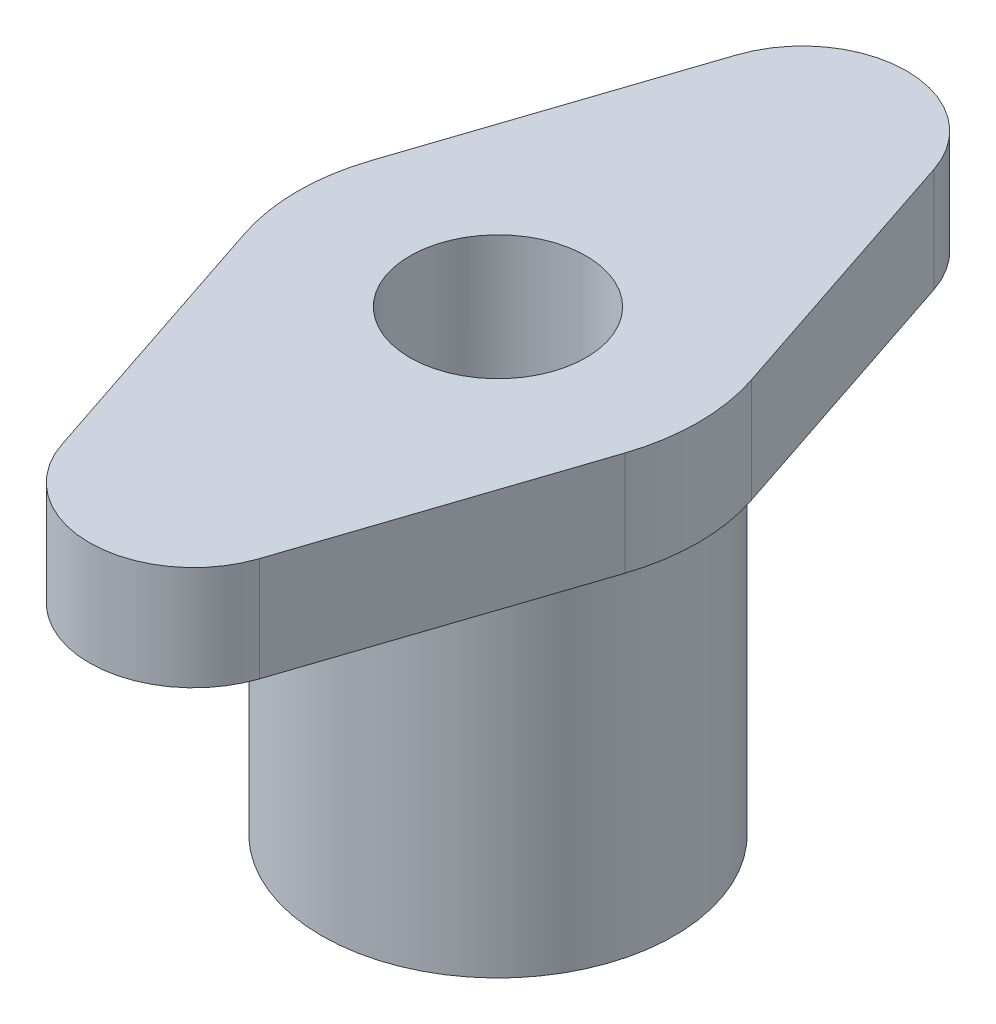
SolidWorks part; units mm, degrees
ref_plane "Front Plane" through (0, 0, 0) normal (0, 0, 1) x (1, 0, 0)
ref_plane "Top Plane" through (0, 0, 0) normal (0, 1, 0) x (1, 0, 0)
ref_plane "Right Plane" through (0, 0, 0) normal (1, 0, 0) x (0, 0, -1)
sketch "Sketch1" plane through (0, 0, 0) normal (0, 1, 0) x (1, 0, 0)
  circle A0 centre (0, 0) radius 22
  dimension "D1" = 44
extrude "Boss-Extrude1" add sketch "Sketch1" along normal blind 44
sketch "Sketch2" plane through (0, 44, 0) normal (0, 1, 0) x (1, 0, 0)
  line L0 (-12.3348, 42.1053) -> (-23.7207, 7.8947)
  line L1 (0, -24.2) -> (0, 24.2) construction
  line L2 (12.3348, 42.1053) -> (23.7207, 7.8947)
  line L3 (-24.2, 0) -> (24.2, 0) construction
  line L4 (12.3348, -42.1053) -> (23.7207, -7.8947)
  line L5 (-12.3348, -42.1053) -> (-23.7207, -7.8947)
  arc A0 (12.3348, 42.1053) -> (-12.3348, 42.1053) centre (0, 38) ccw
  arc A1 (-23.7207, 7.8947) -> (-23.7207, -7.8947) centre (0, 0) ccw
  arc A2 (-12.3348, -42.1053) -> (12.3348, -42.1053) centre (0, -38) ccw
  arc A3 (23.7207, -7.8947) -> (23.7207, 7.8947) centre (0, 0) ccw
  point P1 (-140.8479, -0.1303)
  dimension "D1" = 50
  dimension "D2" = 26
  dimension "D3" = 76
extrude "Boss-Extrude2" add sketch "Sketch2" along normal blind 13
hole_wizard "Hole1" positions "Sketch3" profile "Sketch4" legacy end condition through all
sketch "Sketch3" plane through (0, 57, 0) normal (0, 1, 0) x (1, 0, 0)
  point P0 (0, 0)
sketch "Sketch4" plane through (0, 57, 0) normal (1, 0, 0) x (0, 0, 1)
  line L0 (0, 0) -> (0, 57)
  line L1 (0, 57) -> (11, 57)
  line L2 (11, 57) -> (11, 0)
  line L3 (11, 0) -> (0, 0)
  line L4 (0, 110) -> (0, -10) construction
  dimension "Diameter" = 22
  dimension "Depth" = 57
sketch "Sketch5" plane through (0, 0, 0) normal (1, 0, 0) x (0, 0, -1)
  line L0 (0, 0) -> (0, 6.3509)
  line L1 (0, 6.3509) -> (-11, 6.3509)
  line L2 (-11, 6.3509) -> (-22, 0)
  line L3 (-22, 0) -> (0, 0)
  line L4 (-22, 0) -> (22, 0) construction
  line L5 (0, 0) -> (-36.3328, 0) construction
  point P3 (-22, 0)
  dimension "D1" = 30
  dimension "D2" = 11
revolve "Cut-Revolve1" cut sketch "Sketch5" angle 360 about L0
